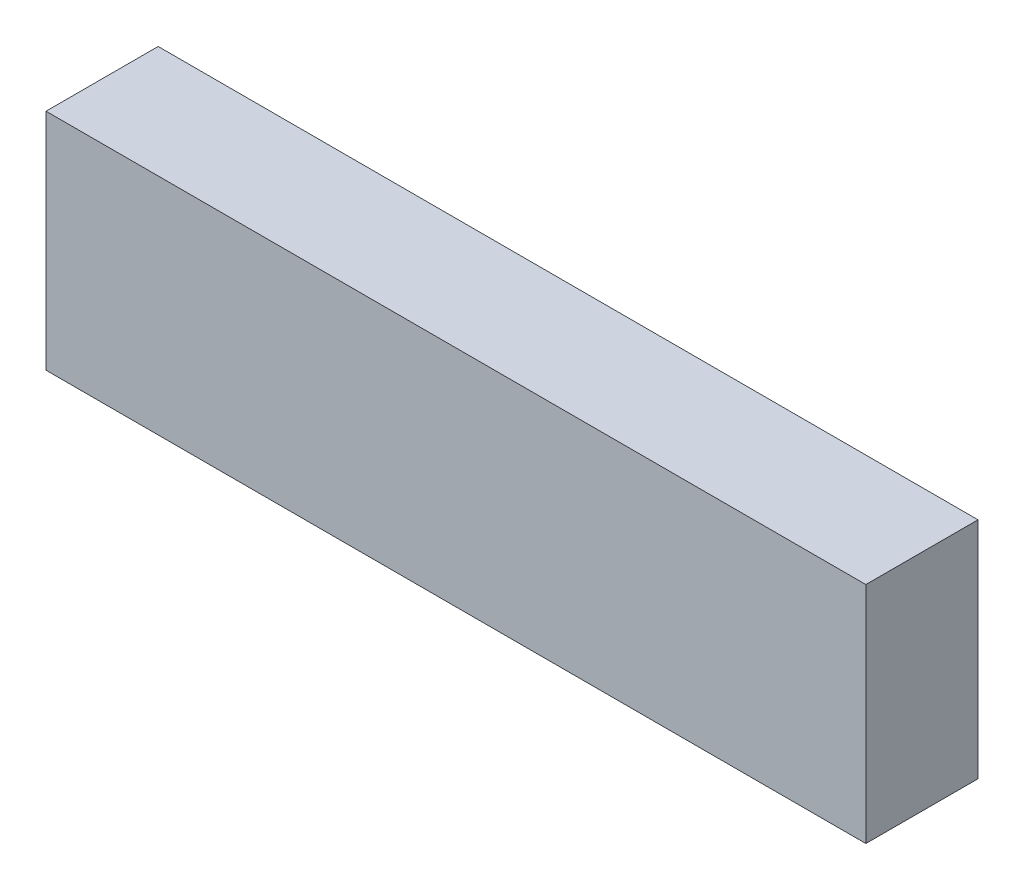
SolidWorks part; units mm, degrees
ref_plane "Front Plane" through (0, 0, 0) normal (0, 0, 1) x (1, 0, 0)
ref_plane "Top Plane" through (0, 0, 0) normal (0, 1, 0) x (1, 0, 0)
ref_plane "Right Plane" through (0, 0, 0) normal (1, 0, 0) x (0, 0, -1)
sketch "Sketch1" plane through (0, 0, 0) normal (0, 0, 1) x (1, 0, 0)
  line L1 (0, 0) -> (73.1, 0)
  line L2 (0, 0) -> (0, 20)
  line L3 (0, 20) -> (73.1, 20)
  line L4 (73.1, 0) -> (73.1, 20)
extrude "Boss-Extrude1" add sketch "Sketch1" against normal blind 10
